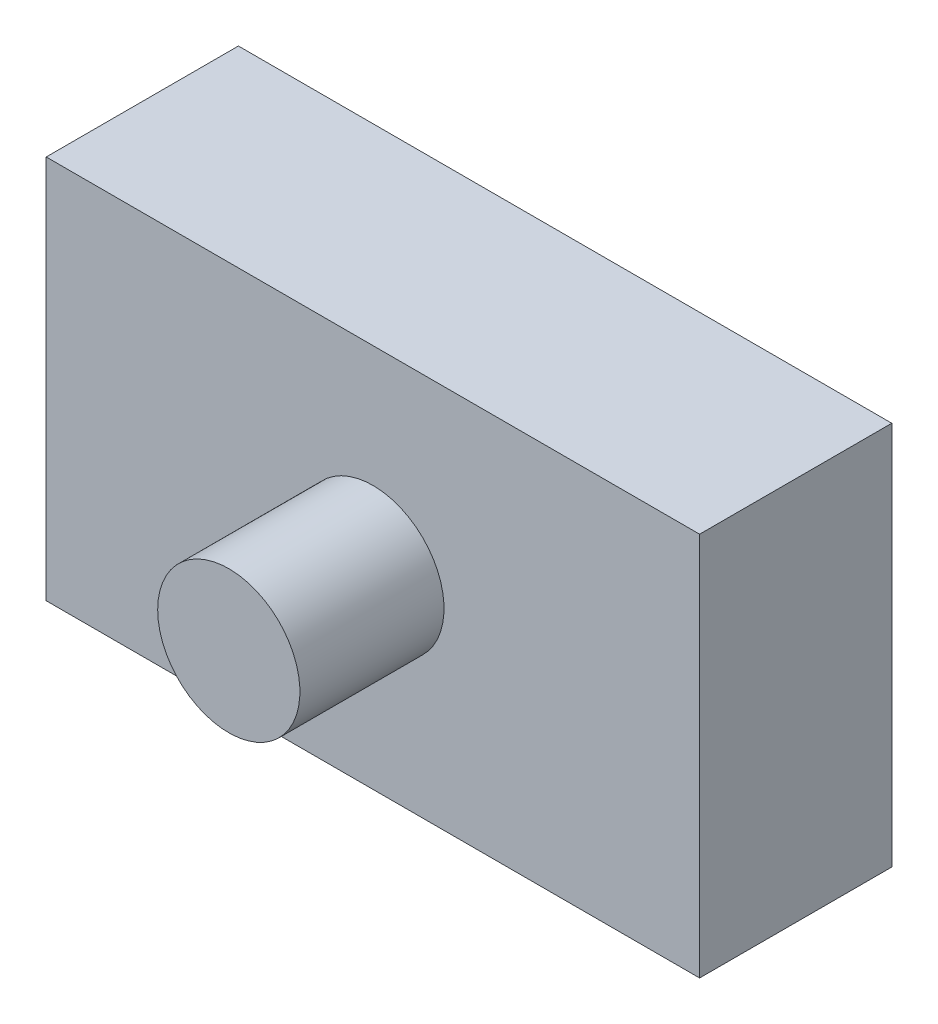
SolidWorks part; units mm, degrees
ref_plane "Front Plane" through (0, 0, 0) normal (0, 0, 1) x (1, 0, 0)
ref_plane "Top Plane" through (0, 0, 0) normal (0, 1, 0) x (1, 0, 0)
ref_plane "Right Plane" through (0, 0, 0) normal (1, 0, 0) x (0, 0, -1)
sketch "Sketch2" plane through (0, 0, 0) normal (0, 0, 1) x (1, 0, 0)
  line L1 (-21.59, -12.7) -> (21.59, -12.7)
  line L2 (-21.59, -12.7) -> (-21.59, 12.7)
  line L3 (-21.59, 12.7) -> (21.59, 12.7)
  line L4 (21.59, -12.7) -> (21.59, 12.7)
  line L5 (-21.59, -12.7) -> (21.59, 12.7) construction
  line L6 (-21.59, 12.7) -> (21.59, -12.7) construction
  point P0 (0, 0)
  dimension "D1" = 43.18
  dimension "D2" = 25.4
extrude "Boss-Extrude3" add sketch "Sketch2" against normal blind 12.7
sketch "Sketch4" plane through (0, 0, 0) normal (0, 0, 1) x (1, 0, 0)
  circle A0 centre (0, 0) radius 4.699
  dimension "D1" = 9.398
extrude "Boss-Extrude4" add sketch "Sketch4" along normal blind 9.525
